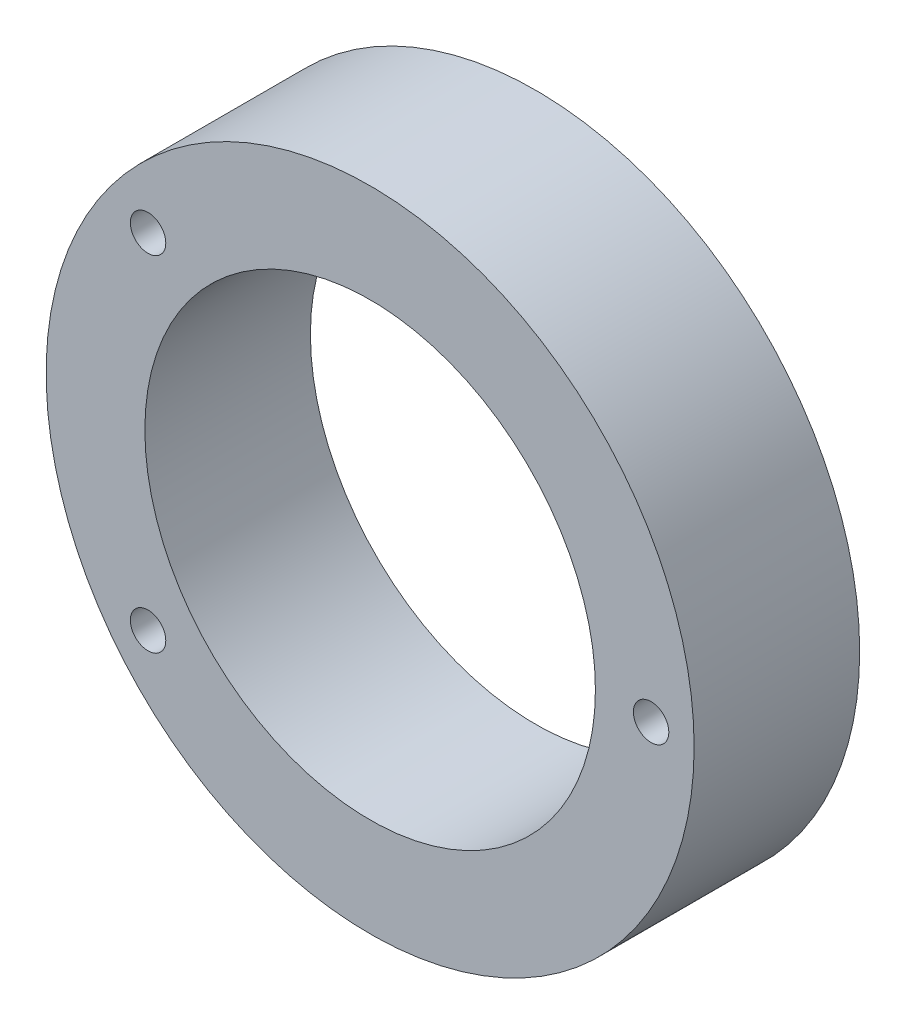
SolidWorks part; units mm, degrees
ref_plane "Front Plane" through (0, 0, 0) normal (0, 0, 1) x (1, 0, 0)
ref_plane "Top Plane" through (0, 0, 0) normal (0, 1, 0) x (1, 0, 0)
ref_plane "Right Plane" through (0, 0, 0) normal (1, 0, 0) x (0, 0, -1)
sketch "Sketch1" plane through (0, 0, 0) normal (0, 0, 1) x (1, 0, 0)
  line L0 (-21.9327, 17.0005) -> (0, 0) construction
  line L1 (0, 0) -> (-21.9327, -17.0005) construction
  line L2 (0, 0) -> (27.75, 0) construction
  line L3 (-21.9327, 17.0005) -> (-21.9327, -17.0005) construction
  circle A0 centre (0, 0) radius 22.25
  circle A1 centre (0, 0) radius 32
  circle A2 centre (-21.9327, 17.0005) radius 1.75
  circle A3 centre (-21.9327, -17.0005) radius 1.75
  circle A4 centre (27.75, 0) radius 1.75
  dimension "D1" = 44.5
  dimension "D2" = 64
  dimension "D5" = 3.5
  dimension "D3" = 75.56
  dimension "D4" = 27.75
extrude "Boss-Extrude1" add sketch "Sketch1" along normal blind 16.35
